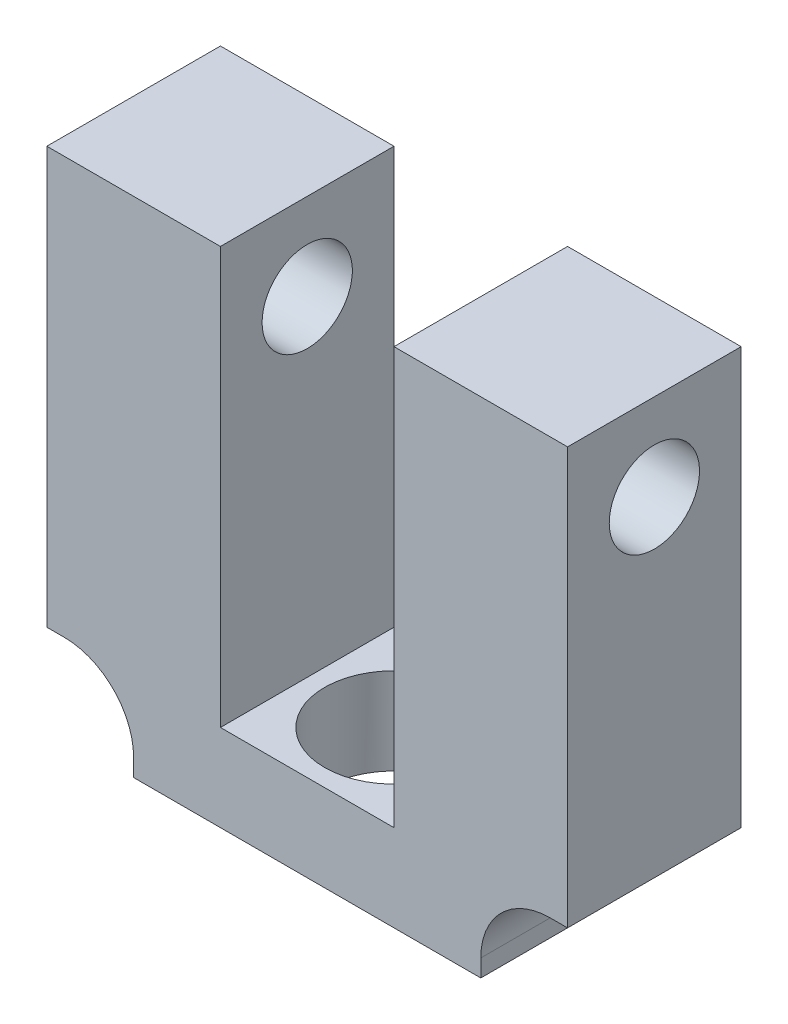
SolidWorks part; units mm, degrees
ref_plane "Front Plane" through (0, 0, 0) normal (0, 0, 1) x (1, 0, 0)
ref_plane "Top Plane" through (0, 0, 0) normal (0, 1, 0) x (1, 0, 0)
ref_plane "Right Plane" through (0, 0, 0) normal (1, 0, 0) x (0, 0, -1)
sketch "Sketch1" plane through (0, 0, 0) normal (0, 1, 0) x (1, 0, 0)
  line L0 (0, 0) -> (12.7, 0)
  line L1 (0, 0) -> (0, 6.35)
  line L2 (12.7, 0) -> (12.7, 6.35)
  line L3 (0, 6.35) -> (12.7, 6.35)
extrude "Boss-Extrude1" add sketch "Sketch1" along normal blind 3.175
sketch "Sketch2" plane through (0, 3.175, 0) normal (0, 1, 0) x (1, 0, 0)
  line L0 (6.35, 6.35) -> (3.175, 6.35) construction
  line L1 (12.7, 6.35) -> (0, 6.35) construction
  line L2 (6.35, 6.35) -> (9.525, 6.35) construction
  line L3 (3.175, 6.35) -> (3.175, 0)
  line L4 (3.175, 6.35) -> (-3.175, 6.35)
  line L5 (3.175, 0) -> (-3.175, 0)
  line L6 (-3.175, 6.35) -> (-3.175, 0)
  line L7 (0, 0) -> (12.7, 0) construction
  line L8 (9.525, 6.35) -> (9.525, 0)
  line L9 (9.525, 6.35) -> (15.875, 6.35)
  line L10 (9.525, 0) -> (15.875, 0)
  line L11 (15.875, 6.35) -> (15.875, 0)
extrude "Boss-Extrude2" add sketch "Sketch2" along normal blind 15.24
fillet "Fillet1" radius 2.54 2 edges at (12.7, 3.175, -3.175) (0, 3.175, -3.175)
sketch "Sketch3" plane through (-3.175, 0, 0) normal (-1, 0, 0) x (0, 0, 1)
  line L0 (-3.175, 18.415) -> (-3.175, 15.24) construction
  line L1 (-6.35, 18.415) -> (0, 18.415) construction
  circle A0 centre (-3.175, 15.24) radius 1.651
extrude "Cut-Extrude1" cut sketch "Sketch3" against normal blind 22.606
sketch "Sketch4" plane through (0, 3.175, 0) normal (0, 1, 0) x (1, 0, 0)
  line L0 (6.35, 6.35) -> (6.35, 3.175) construction
  line L1 (9.525, 6.35) -> (3.175, 6.35) construction
  circle A0 centre (6.35, 3.175) radius 2.54
extrude "Cut-Extrude2" cut sketch "Sketch4" against normal blind 22.606
